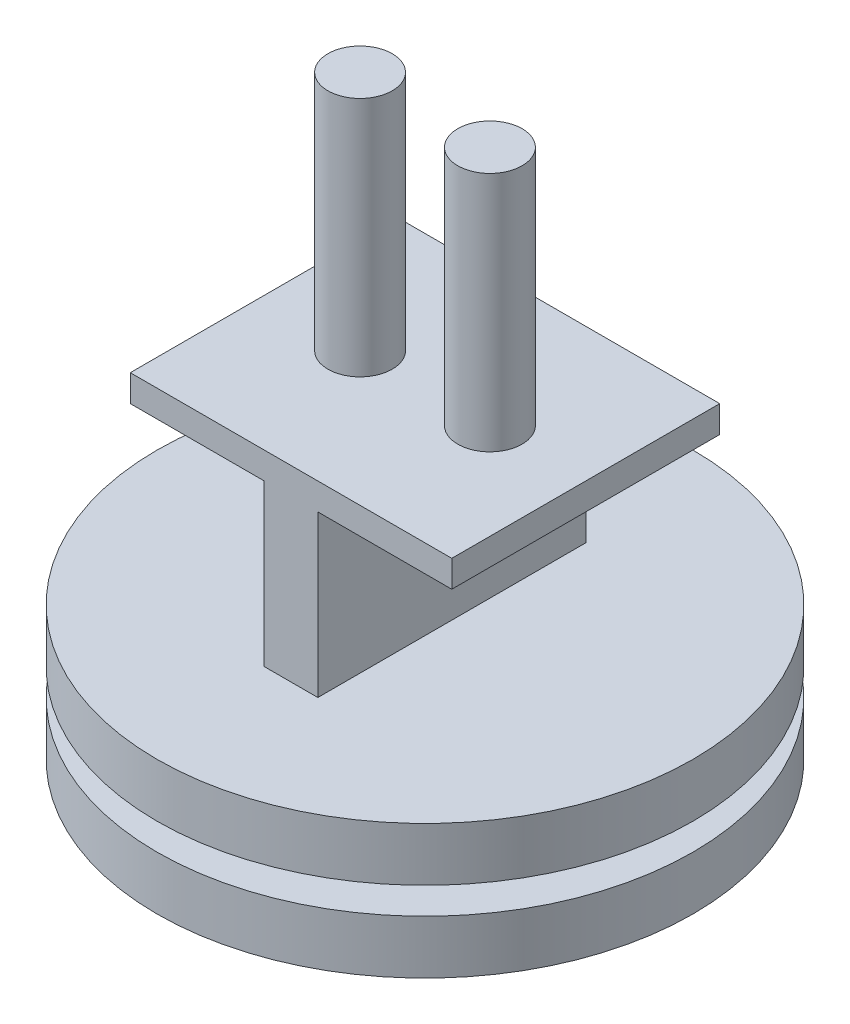
SolidWorks part; units mm, degrees
ref_plane "前视基准面" through (0, 0, 0) normal (0, 0, 1) x (1, 0, 0)
ref_plane "上视基准面" through (0, 0, 0) normal (0, 1, 0) x (1, 0, 0)
ref_plane "右视基准面" through (0, 0, 0) normal (1, 0, 0) x (0, 0, -1)
sketch "草图1" plane through (0, 0, 0) normal (0, 1, 0) x (1, 0, 0)
  circle A0 centre (0, 0) radius 50
extrude "凸台-拉伸1" add sketch "草图1" along normal blind 10
sketch "草图2" plane through (0, 10, 0) normal (0, 1, 0) x (1, 0, 0)
  circle A0 centre (0, 0) radius 10
extrude "凸台-拉伸2" add sketch "草图2" along normal blind 5
sketch "草图3" plane through (0, 15, 0) normal (0, 1, 0) x (1, 0, 0)
  circle A0 centre (0, 0) radius 50
extrude "凸台-拉伸3" add sketch "草图3" along normal blind 10
sketch "草图4" plane through (0, 25, 0) normal (0, 1, 0) x (1, 0, 0)
  line L1 (-5, 25) -> (5, 25)
  line L2 (-5, 25) -> (-5, -25)
  line L3 (-5, -25) -> (5, -25)
  line L4 (5, 25) -> (5, -25)
  line L5 (-5, 25) -> (5, -25) construction
  line L6 (-5, -25) -> (5, 25) construction
  point P0 (0, 0)
extrude "凸台-拉伸4" add sketch "草图4" along normal blind 30
sketch "草图5" plane through (0, 55, 0) normal (0, 1, 0) x (1, 0, 0)
  line L1 (-30, -25) -> (30, -25)
  line L2 (-30, -25) -> (-30, 25)
  line L3 (-30, 25) -> (30, 25)
  line L4 (30, -25) -> (30, 25)
  line L5 (-30, -25) -> (30, 25) construction
  line L6 (-30, 25) -> (30, -25) construction
  point P0 (0, 0)
extrude "凸台-拉伸5" add sketch "草图5" along normal blind 5
sketch "草图6" plane through (0, 60, 0) normal (0, 1, 0) x (1, 0, 0)
  line L0 (0, 0) -> (0, 53.1336) construction
  circle A0 centre (12.1182, 0) radius 6
  circle A1 centre (-12.1182, 0) radius 6
  point P5 (0, 0)
  point P6 (0, 0)
extrude "凸台-拉伸6" add sketch "草图6" along normal blind 45
